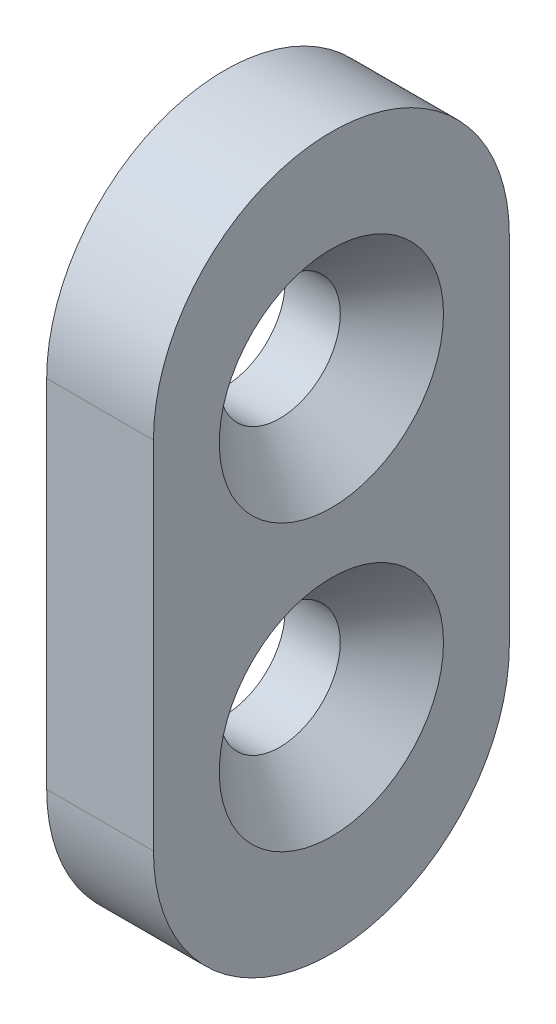
SolidWorks part; units mm, degrees
material "POLYURETHANE (11671)"
ref_plane "Front Plane" through (0, 0, 0) normal (0, 0, 1) x (1, 0, 0)
ref_plane "Top Plane" through (0, 0, 0) normal (0, 1, 0) x (1, 0, 0)
ref_plane "Right Plane" through (0, 0, 0) normal (1, 0, 0) x (0, 0, -1)
sketch "Sketch1" plane through (0, 0, 0) normal (1, 0, 0) x (0, 0, -1)
  line L0 (0, 5) -> (0, -5) construction
  line L1 (0, 55) -> (0, -55) construction
  line L2 (5, 5) -> (5, -5)
  line L3 (-5, 5) -> (-5, -5)
  line L4 (55, 0) -> (-55, 0) construction
  arc A0 (5, 5) -> (-5, 5) centre (0, 5) ccw
  arc A1 (-5, -5) -> (5, -5) centre (0, -5) ccw
  point P5 (0, 0)
  dimension "D1" = 10
  dimension "D2" = 10
extrude "Boss-Extrude1" add sketch "Sketch1" along normal mid plane 3
hole_wizard "CSK for M3 Countersunk Flat Head Screw1" positions "Sketch2" profile "Sketch3" countersink size "M3" standard "ISO" end condition through all
sketch "Sketch2" plane through (1.5, 0, 0) normal (1, 0, 0) x (0, 0, -1)
  line L0 (0, -4) -> (0, 4) construction
  line L2 (0, 55) -> (0, -55) construction
  line L3 (55, 0) -> (-55, 0) construction
  point P0 (0, 4)
  point P2 (0, -4)
  point P12 (0, 0)
  dimension "D1" = 0
  dimension "D2" = 8
sketch "Sketch3" plane through (1.5, 4, 0) normal (0, 1, 0) x (0, 0, -1)
  line L0 (0, 0) -> (0, 3)
  line L1 (0, 3) -> (1.7, 3)
  line L2 (1.7, 3) -> (1.7, 1.45)
  line L3 (1.7, 1.45) -> (3.15, 0)
  line L5 (3.15, 0) -> (0, 0)
  line L6 (-1.7, 1.45) -> (-3.15, 0) construction
  line L11 (0, -6.35) -> (0, 107.95) construction
  dimension "Thru Hole Dia." = 3.4
  dimension "Thru Hole Depth" = 3
  dimension "Near C'Sink Dia." = 6.3
  dimension "Near C'Sink Angle" = 90
